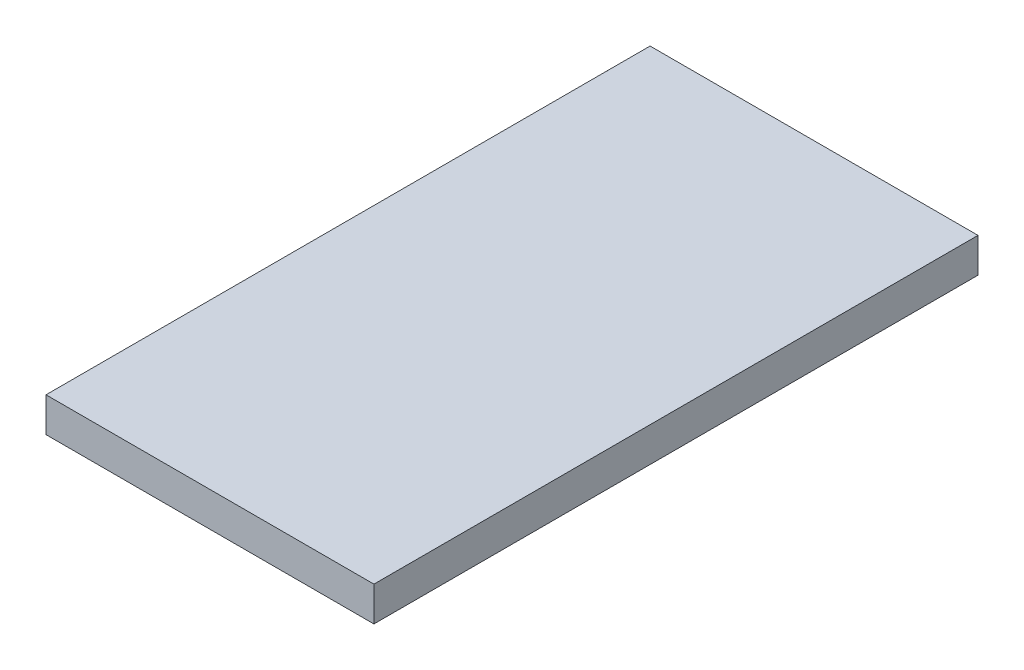
SolidWorks part; units mm, degrees
ref_plane "Alzado" through (0, 0, 0) normal (0, 0, 1) x (1, 0, 0)
ref_plane "Planta" through (0, 0, 0) normal (0, 1, 0) x (1, 0, 0)
ref_plane "Vista lateral" through (0, 0, 0) normal (1, 0, 0) x (0, 0, -1)
sketch "Croquis1" plane through (0, 0, 0) normal (0, 1, 0) x (1, 0, 0)
  line L1 (-9.5, -17.5) -> (9.5, -17.5)
  line L2 (-9.5, -17.5) -> (-9.5, 17.5)
  line L3 (-9.5, 17.5) -> (9.5, 17.5)
  line L4 (9.5, -17.5) -> (9.5, 17.5)
  line L5 (-9.5, -17.5) -> (9.5, 17.5) construction
  line L6 (-9.5, 17.5) -> (9.5, -17.5) construction
  point P0 (0, 0)
  dimension "D1" = 19
  dimension "D2" = 35
extrude "Saliente-Extruir4" add sketch "Croquis1" along normal blind 2
